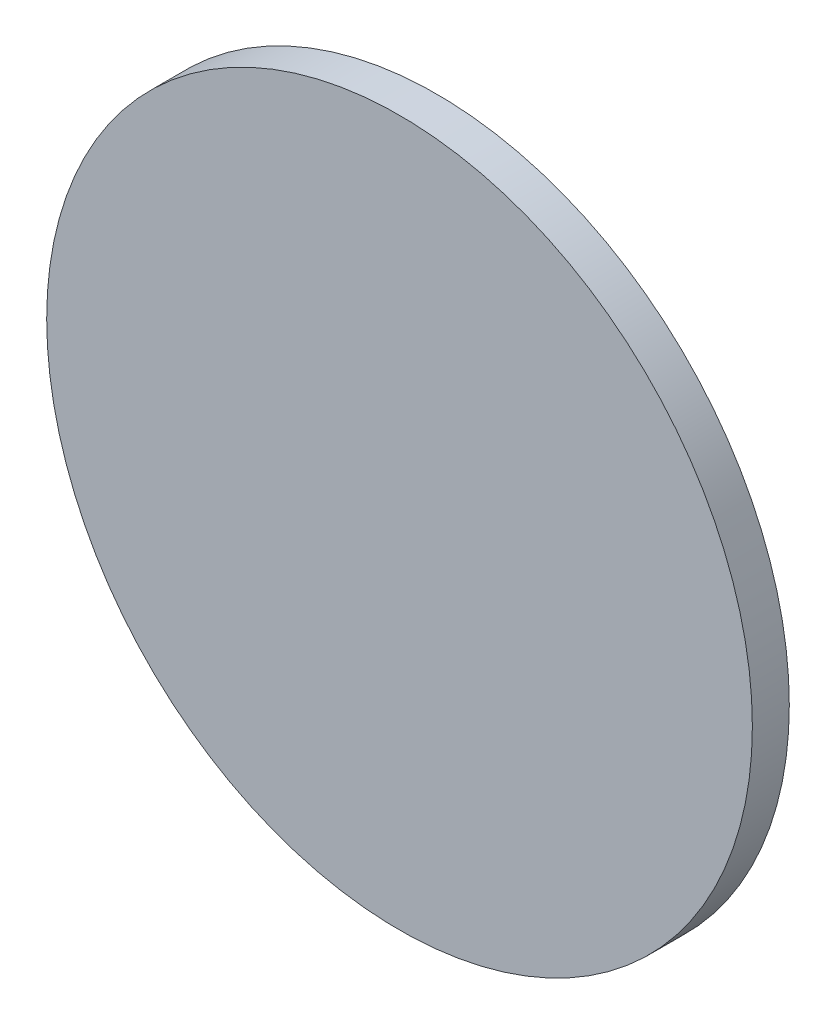
SolidWorks part; units mm, degrees
ref_plane "Plan de face" through (0, 0, 0) normal (0, 0, 1) x (1, 0, 0)
ref_plane "Plan de dessus" through (0, 0, 0) normal (0, 1, 0) x (1, 0, 0)
ref_plane "Plan de droite" through (0, 0, 0) normal (1, 0, 0) x (0, 0, -1)
sketch "Esquisse1" plane through (0, 0, 0) normal (0, 0, 1) x (1, 0, 0)
  circle A0 centre (0, 0) radius 47.75
  dimension "D1" = 95.5
extrude "Boss.-Extru.1" add sketch "Esquisse1" along normal blind 5
